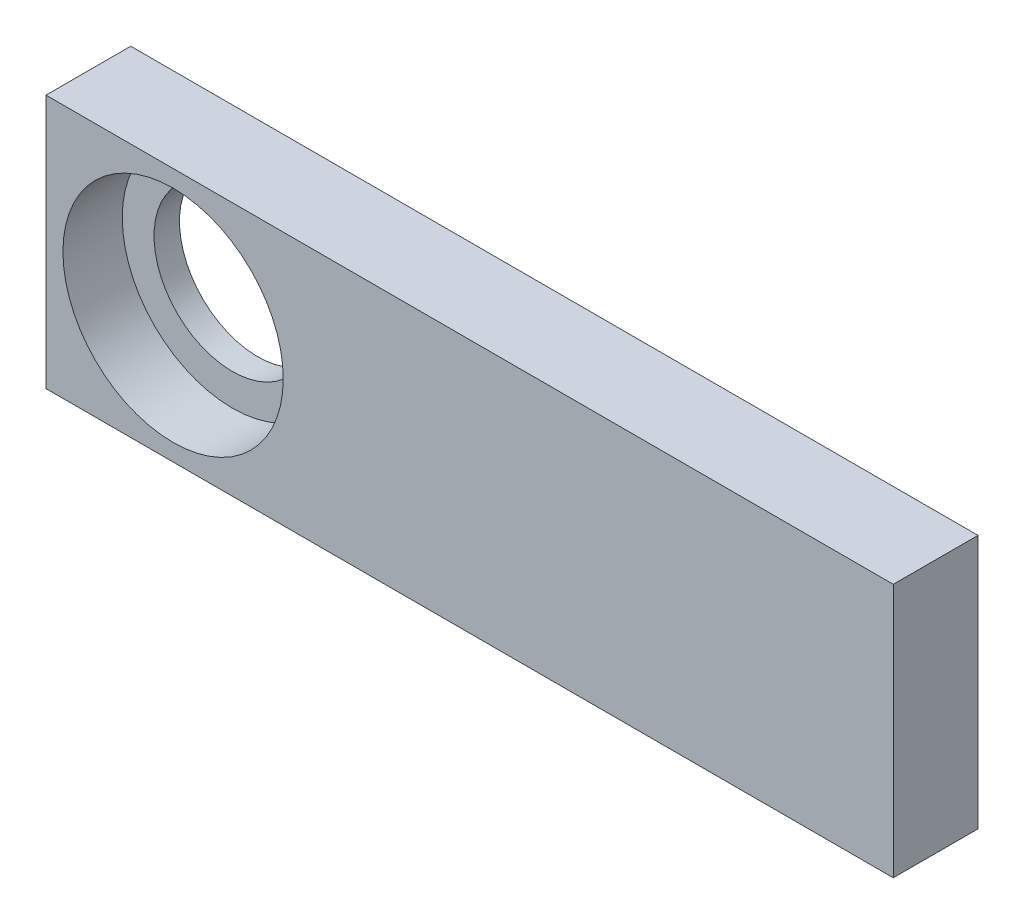
SolidWorks part; units mm, degrees
ref_plane "Plano frontal" through (0, 0, 0) normal (0, 0, 1) x (1, 0, 0)
ref_plane "Plano superior" through (0, 0, 0) normal (0, 1, 0) x (1, 0, 0)
ref_plane "Plano direito" through (0, 0, 0) normal (1, 0, 0) x (0, 0, -1)
sketch "Esboço1" plane through (0, 0, 0) normal (0, 0, 1) x (1, 0, 0)
  line L1 (0, 30) -> (100, 30)
  line L2 (0, 30) -> (0, 0)
  line L3 (0, 0) -> (100, 0)
  line L4 (100, 30) -> (100, 0)
  dimension "D1" = 30
  dimension "D2" = 100
extrude "Ressalto-extrusão1" add sketch "Esboço1" along normal blind 10
sketch "Esboço2" plane through (0, 0, 10) normal (0, 0, 1) x (1, 0, 0)
  line L0 (30, 30) -> (30, 0) construction
  line L1 (100, 30) -> (0, 30) construction
  line L2 (0, 0) -> (100, 0) construction
  line L3 (0, 30) -> (0, 0) construction
  line L4 (30, 30) -> (0, 0) construction
  circle A0 centre (15, 15) radius 13
  dimension "D2" = 26
  dimension "D1" = 30
extrude "Corte-extrusão1" cut sketch "Esboço2" against normal blind 7
sketch "Esboço4" plane through (0, 0, 3) normal (0, 0, 1) x (1, 0, 0)
  circle A0 centre (15, 15) radius 9.25
  dimension "D1" = 18.5
extrude "Corte-extrusão3" cut sketch "Esboço4" against normal through all
sketch "Esboço3" plane through (0, 0, 10) normal (0, 0, 1) x (1, 0, 0)
  line L0 (-50, -11.5) -> (50, -11.5) construction
  line L1 (-50, 18.5) -> (-20, 18.5)
  line L2 (-50, 18.5) -> (-50, -11.5)
  line L3 (-50, -11.5) -> (-20, -11.5)
  line L4 (-20, 18.5) -> (-20, -11.5)
  dimension "D1" = 30
extrude "Corte-extrusão2" cut sketch "Esboço3" against normal blind 2
